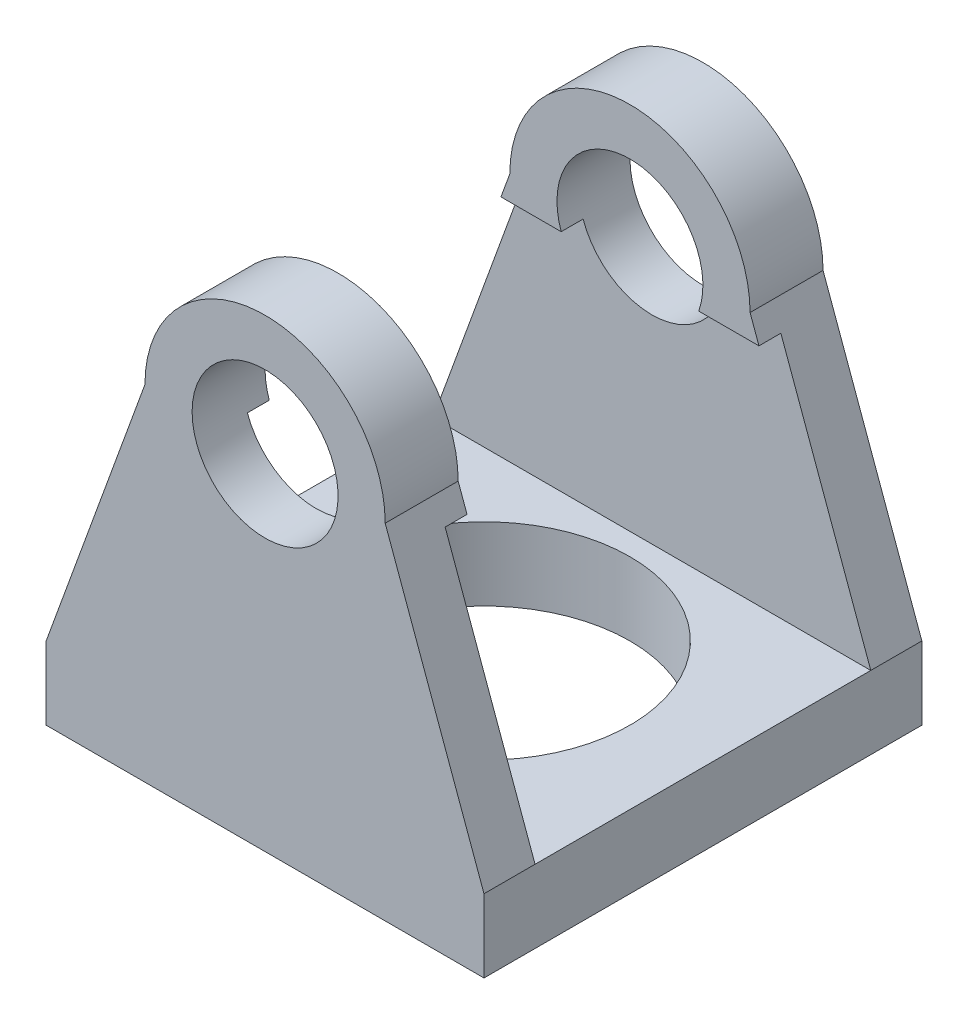
SolidWorks part; units mm, degrees
ref_plane "Front Plane" through (0, 0, 0) normal (0, 0, 1) x (1, 0, 0)
ref_plane "Top Plane" through (0, 0, 0) normal (0, 1, 0) x (1, 0, 0)
ref_plane "Right Plane" through (0, 0, 0) normal (1, 0, 0) x (0, 0, -1)
sketch "Sketch1" plane through (0, 0, 0) normal (0, 1, 0) x (1, 0, 0)
  line L1 (-15, 15) -> (15, 15)
  line L2 (-15, 15) -> (-15, -15)
  line L3 (-15, -15) -> (15, -15)
  line L4 (15, 15) -> (15, -15)
  line L5 (-15, 15) -> (15, -15) construction
  line L6 (-15, -15) -> (15, 15) construction
  point P0 (0, 0)
  dimension "D1" = 30
  dimension "D2" = 30
extrude "Boss-Extrude1" add sketch "Sketch1" along normal blind 5
sketch "Sketch3" plane through (0, 0, 15) normal (0, 0, 1) x (1, 0, 0)
  line L2 (-15, 5) -> (-8.2298, 23.601)
  line L3 (-15, 5) -> (15, 5) construction
  line L4 (15, 5) -> (8.2298, 23.601)
  line L5 (-15, 5) -> (15, 5)
  arc A1 (8.2298, 23.601) -> (-8.2298, 23.601) centre (0, 23.601) ccw
  dimension "D1" = 70
  dimension "D2" = 70
extrude "Boss-Extrude2" add sketch "Sketch3" against normal blind 5
sketch "Sketch5" plane through (0, 0, -15) normal (0, 0, -1) x (-1, 0, 0)
  line L0 (-15, 5) -> (-8.2298, 23.601)
  line L1 (-15, 5) -> (15, 5)
  line L2 (15, 5) -> (8.2298, 23.601)
  arc A0 (8.2298, 23.601) -> (-8.2298, 23.601) centre (0, 23.601) ccw
extrude "Boss-Extrude3" add sketch "Sketch5" against normal blind 5
sketch "Sketch6" plane through (0, 0, -15) normal (0, 0, -1) x (-1, 0, 0)
  circle A0 centre (0, 23.601) radius 5
extrude "Cut-Extrude1" cut sketch "Sketch6" against normal blind 38
sketch "Sketch7" plane through (0, 0, 0) normal (0, -1, 0) x (1, 0, 0)
  circle A0 centre (0, 0) radius 10
extrude "Cut-Extrude2" cut sketch "Sketch7" against normal up to vertex (5 mm away)
sketch "Sketch8" plane through (15, 0, 0) normal (1, 0, 0) x (0, 0, -1)
  line L0 (10, 5) -> (15, 5) construction
  line L1 (-11.5004, 21.928) -> (11.5004, 21.928)
  line L2 (-11.5004, 21.928) -> (-11.5004, 5)
  line L3 (-11.5004, 5) -> (11.5004, 5)
  line L4 (11.5004, 21.928) -> (11.5004, 5)
  line L5 (-11.5004, 21.928) -> (11.5004, 5) construction
  line L6 (-11.5004, 5) -> (11.5004, 21.928) construction
  point P0 (0, 13.464)
extrude "Cut-Extrude3" cut sketch "Sketch8" against normal blind 30
